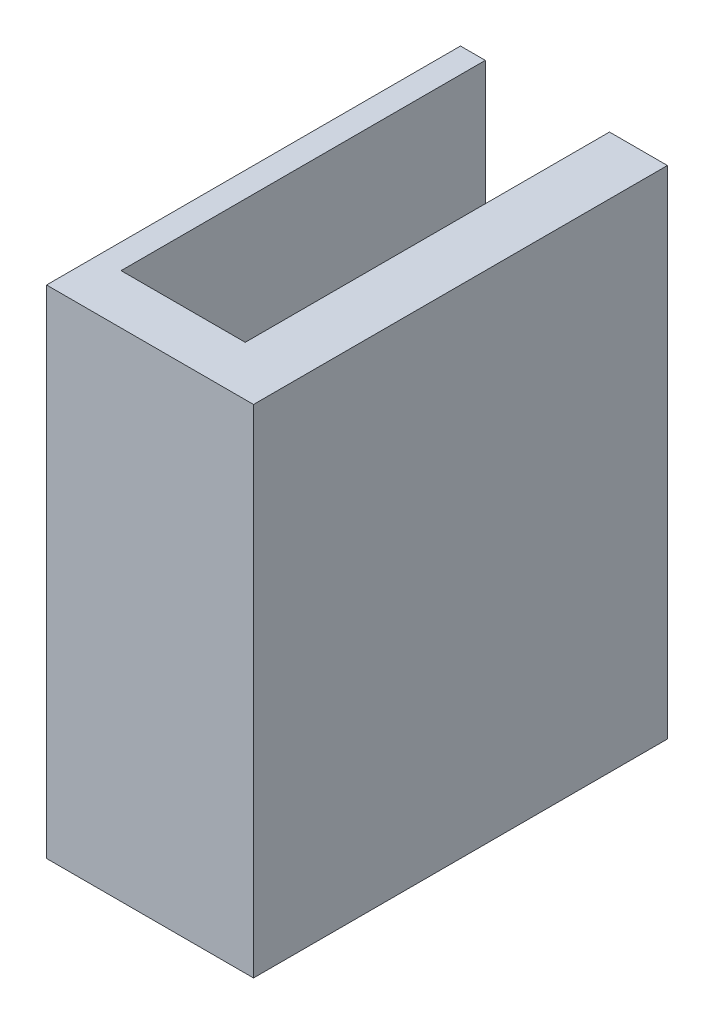
SolidWorks part; units mm, degrees
ref_plane "前视基准面" through (0, 0, 0) normal (0, 0, 1) x (1, 0, 0)
ref_plane "上视基准面" through (0, 0, 0) normal (0, 1, 0) x (1, 0, 0)
ref_plane "右视基准面" through (0, 0, 0) normal (1, 0, 0) x (0, 0, -1)
sketch "草图1" plane through (0, 0, 0) normal (0, 1, 0) x (1, 0, 0)
  line L0 (-9.5, 25) -> (-9.5, -19)
  line L1 (-12.5, 25) -> (-9.5, 25)
  line L2 (-12.5, 25) -> (-12.5, -25)
  line L3 (-12.5, -25) -> (12.5, -25)
  line L4 (12.5, 25) -> (12.5, -25)
  line L5 (-12.5, 25) -> (12.5, -25) construction
  line L6 (-12.5, -25) -> (12.5, 25) construction
  line L7 (-9.5, -19) -> (5.5, -19)
  line L8 (5.5, -19) -> (5.5, 25)
  line L9 (5.5, 25) -> (12.5, 25)
  point P0 (0, 0)
  point P11 (17.6735, -18.6054)
  dimension "D1" = 25
  dimension "D2" = 50
  dimension "D3" = 3
  dimension "D4" = 15
extrude "凸台-拉伸1" add sketch "草图1" along normal blind 60
